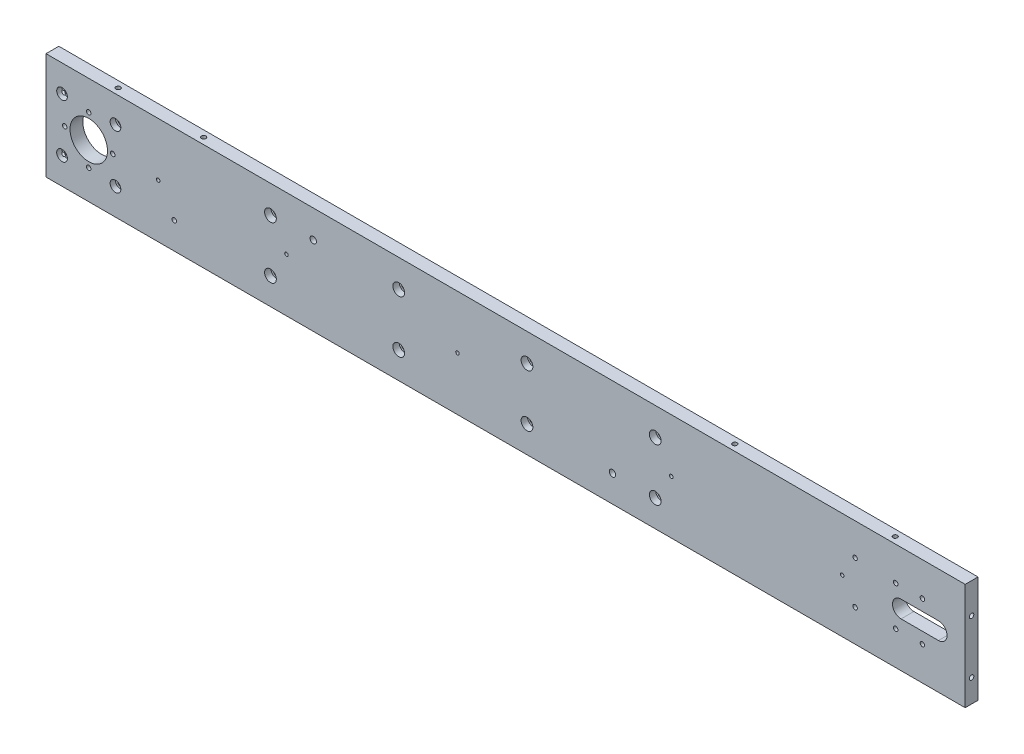
SolidWorks part; units mm, degrees
material "SKD11淬火HRC56-60"
ref_plane "前基準面" through (0, 0, 0) normal (0, 0, 1) x (1, 0, 0)
ref_plane "上基準面" through (0, 0, 0) normal (0, 1, 0) x (1, 0, 0)
ref_plane "右基準面" through (0, 0, 0) normal (1, 0, 0) x (0, 0, -1)
sketch "草图1" plane through (0, 0, 0) normal (0, 0, 1) x (1, 0, 0)
  line L1 (0, 0) -> (860, 0)
  line L2 (0, 0) -> (0, 100)
  line L3 (0, 100) -> (860, 100)
  line L4 (860, 0) -> (860, 100)
  dimension "D1" = 860
  dimension "D2" = 100
extrude "凸台-拉伸1" add sketch "草图1" along normal blind 12
sketch "草图2" plane through (0, 0, 12) normal (0, 0, 1) x (1, 0, 0)
  line L0 (0, 50) -> (860, 50) construction
  line L1 (0, 100) -> (0, 0) construction
  line L2 (430, 0) -> (430, 100) construction
  line L3 (0, 0) -> (860, 0) construction
  line L4 (860, 100) -> (0, 100) construction
  line L5 (860, 0) -> (860, 100) construction
  line L6 (800, 50) -> (835, 50) construction
  line L7 (800, 58) -> (835, 58)
  line L8 (800, 42) -> (835, 42)
  circle A0 centre (40, 50) radius 17.55
  arc A1 (800, 58) -> (800, 42) centre (800, 50) ccw
  arc A2 (835, 42) -> (835, 58) centre (835, 50) ccw
  point P14 (817.5, 50)
  dimension "D1" = 35.1
  dimension "D2" = 390
  dimension "D3" = 8
  dimension "D4" = 35
  dimension "D5" = 370
extrude "切除-拉伸1" cut sketch "草图2" against normal through all
hole_wizard "M5 螺纹孔1" positions "草图4" profile "草图3" tap size "M5" standard "ISO"
sketch "草图4" plane through (0, 100, 0) normal (0, 1, 0) x (-1, 0, 0)
  point P0 (-141.5, 6)
  point P5 (-61.5, 6)
  point P8 (-788.5, 6)
  point P11 (-638.5, 6)
sketch "草图3" plane through (141.5, 100, 6) normal (1, 0, 0) x (0, 0, 1)
  line L0 (0, 0) -> (0, 13.6618)
  line L1 (0, 13.6618) -> (2.1, 12.4)
  line L2 (2.1, 12.4) -> (2.1, 0)
  line L5 (2.1, 0) -> (0, 0)
  line L10 (0, 13.6618) -> (-2.1, 12.4) construction
  line L11 (0, -6.35) -> (0, 107.95) construction
  dimension "螺纹孔钻头直径" = 4.2
  dimension "螺纹孔钻头深度" = 12.4
  dimension "导头角度" = 118
cosmetic thread "孔螺蚊线1" parameters "D1"=10, "D2"=5
cosmetic thread "孔螺蚊线2" parameters "D1"=10, "D2"=5
cosmetic thread "孔螺蚊线3" parameters "D1"=10, "D2"=5
cosmetic thread "孔螺蚊线4" parameters "D1"=10, "D2"=5
hole_wizard "M5 螺纹孔2" positions "草图6" profile "草图5" tap size "M5" standard "ISO"
sketch "草图6" plane through (0, 0, 0) normal (-1, 0, 0) x (0, 0, 1)
  point P0 (6, 71.5)
  point P4 (6, 21.5)
sketch "草图5" plane through (0, 71.5, 6) normal (0, 1, 0) x (0, 0, 1)
  line L0 (0, 0) -> (0, 13.6618)
  line L1 (0, 13.6618) -> (2.1, 12.4)
  line L2 (2.1, 12.4) -> (2.1, 0)
  line L5 (2.1, 0) -> (0, 0)
  line L10 (0, 13.6618) -> (-2.1, 12.4) construction
  line L11 (0, -6.35) -> (0, 107.95) construction
  dimension "螺纹孔钻头直径" = 4.2
  dimension "螺纹孔钻头深度" = 12.4
  dimension "导头角度" = 118
cosmetic thread "孔螺蚊线5" parameters "D1"=10, "D2"=5
cosmetic thread "孔螺蚊线6" parameters "D1"=10, "D2"=5
hole_wizard "M5 螺纹孔3" positions "草图8" profile "草图7" tap size "M5" standard "ISO"
sketch "草图8" plane through (860, 0, 0) normal (1, 0, 0) x (0, 0, -1)
  point P0 (-6, 71.5)
  point P4 (-6, 21.5)
sketch "草图7" plane through (860, 71.5, 6) normal (0, 1, 0) x (0, 0, -1)
  line L0 (0, 0) -> (0, 13.6618)
  line L1 (0, 13.6618) -> (2.1, 12.4)
  line L2 (2.1, 12.4) -> (2.1, 0)
  line L5 (2.1, 0) -> (0, 0)
  line L10 (0, 13.6618) -> (-2.1, 12.4) construction
  line L11 (0, -6.35) -> (0, 107.95) construction
  dimension "螺纹孔钻头直径" = 4.2
  dimension "螺纹孔钻头深度" = 12.4
  dimension "导头角度" = 118
cosmetic thread "孔螺蚊线7" parameters "D1"=10, "D2"=5
cosmetic thread "孔螺蚊线8" parameters "D1"=10, "D2"=5
sketch "草图9" plane through (0, 0, 12) normal (0, 0, 1) x (1, 0, 0)
  line L0 (860, 100) -> (0, 100) construction
  line L1 (0, 100) -> (0, 0) construction
  circle A0 centre (250, 74) radius 3
  circle A1 centre (530, 25) radius 3
  dimension "D1" = 26
  dimension "D2" = 6
  dimension "D3" = 250
  dimension "D4" = 280
  dimension "D5" = 75
extrude "切除-拉伸2" cut sketch "草图9" against normal through all
hole_wizard "M6 六角凹头螺钉的柱形沉头孔1" positions "草图11" profile "草图10" counterbore size "M6" standard "ISO" end condition through all
sketch "草图11" plane through (0, 0, 12) normal (0, 0, 1) x (1, 0, 0)
  line L0 (860, 100) -> (0, 100) construction
  line L1 (0, 100) -> (0, 0) construction
  point P0 (210, 74)
  point P1 (330, 74)
  point P3 (450, 74)
  point P5 (570, 74)
  point P7 (570, 25)
  point P9 (450, 25)
  point P11 (330, 25)
  point P13 (210, 25)
  dimension "D1" = 26
  dimension "D2" = 75
  dimension "D3" = 210
  dimension "D4" = 120
  dimension "D5" = 120
  dimension "D6" = 120
sketch "草图10" plane through (210, 74, 12) normal (1, 0, 0) x (0, -1, 0)
  line L0 (0, 0) -> (0, 12)
  line L1 (0, 12) -> (3.5, 12)
  line L3 (3.5, 12) -> (3.5, 6)
  line L4 (3.5, 6) -> (5.5, 6)
  line L5 (5.5, 6) -> (5.5, 0)
  line L7 (5.5, 0) -> (0, 0)
  line L11 (0, -6.35) -> (0, 107.95) construction
  dimension "通孔孔直径" = 7
  dimension "通孔孔深度" = 12
  dimension "柱形沉头孔直径" = 11
  dimension "柱形沉头孔深度" = 6
hole_wizard "M4 螺纹孔1" positions "草图13" profile "草图12" tap size "M4" standard "ISO"
sketch "草图13" plane through (0, 0, 12) normal (0, 0, 1) x (1, 0, 0)
  point P5 (225, 50)
  point P8 (105, 50)
  point P11 (385, 50)
  point P14 (745, 50)
  point P17 (585, 50)
sketch "草图12" plane through (225, 50, 12) normal (1, 0, 0) x (0, -1, 0)
  line L0 (0, 0) -> (0, 11.0914)
  line L1 (0, 11.0914) -> (1.65, 10.1)
  line L2 (1.65, 10.1) -> (1.65, 0)
  line L5 (1.65, 0) -> (0, 0)
  line L10 (0, 11.0914) -> (-1.65, 10.1) construction
  line L11 (0, -6.35) -> (0, 107.95) construction
  dimension "螺纹孔钻头直径" = 3.3
  dimension "螺纹孔钻头深度" = 10.1
  dimension "导头角度" = 118
cosmetic thread "孔螺蚊线9" parameters "D1"=8, "D2"=4
cosmetic thread "孔螺蚊线10" parameters "D1"=8, "D2"=4
cosmetic thread "孔螺蚊线11" parameters "D1"=8, "D2"=4
cosmetic thread "孔螺蚊线12" parameters "D1"=8, "D2"=4
cosmetic thread "孔螺蚊线13" parameters "D1"=8, "D2"=4
hole_wizard "M5 螺纹孔4" positions "草图15" profile "草图14" tap size "M5" standard "ISO"
sketch "草图15" plane through (0, 0, 0) normal (0, 0, -1) x (-1, 0, 0)
  point P0 (-757, 70)
  point P1 (-757, 30)
sketch "草图14" plane through (757, 70, 0) normal (1, 0, 0) x (0, 1, 0)
  line L0 (0, 0) -> (0, 13.6618)
  line L1 (0, 13.6618) -> (2.1, 12.4)
  line L2 (2.1, 12.4) -> (2.1, 0)
  line L5 (2.1, 0) -> (0, 0)
  line L10 (0, 13.6618) -> (-2.1, 12.4) construction
  line L11 (0, -6.35) -> (0, 107.95) construction
  dimension "螺纹孔钻头直径" = 4.2
  dimension "螺纹孔钻头深度" = 12.4
  dimension "导头角度" = 118
cosmetic thread "孔螺蚊线14" parameters "D1"=10, "D2"=5
cosmetic thread "孔螺蚊线15" parameters "D1"=10, "D2"=5
hole_wizard "M5 螺纹孔5" positions "草图17" profile "草图16" tap size "M5" standard "ISO"
sketch "草图17" plane through (0, 0, 0) normal (0, 0, -1) x (-1, 0, 0)
  line L0 (-860, 0) -> (-860, 100) construction
  line L1 (-860, 100) -> (0, 100) construction
  point P0 (-795, 68.5)
  point P1 (-820, 68.5)
  point P3 (-795, 31.5)
  point P5 (-820, 31.5)
  dimension "D1" = 40
  dimension "D2" = 25
  dimension "D3" = 37
  dimension "D4" = 31.5
sketch "草图16" plane through (795, 68.5, 0) normal (1, 0, 0) x (0, 1, 0)
  line L0 (0, 0) -> (0, 13.6618)
  line L1 (0, 13.6618) -> (2.1, 12.4)
  line L2 (2.1, 12.4) -> (2.1, 0)
  line L5 (2.1, 0) -> (0, 0)
  line L10 (0, 13.6618) -> (-2.1, 12.4) construction
  line L11 (0, -6.35) -> (0, 107.95) construction
  dimension "螺纹孔钻头直径" = 4.2
  dimension "螺纹孔钻头深度" = 12.4
  dimension "导头角度" = 118
cosmetic thread "孔螺蚊线16" parameters "D1"=10, "D2"=5
cosmetic thread "孔螺蚊线17" parameters "D1"=10, "D2"=5
cosmetic thread "孔螺蚊线18" parameters "D1"=10, "D2"=5
cosmetic thread "孔螺蚊线19" parameters "D1"=10, "D2"=5
hole_wizard "M5 六角凹头螺钉的柱形沉头孔1" positions "草图19" profile "草图18" counterbore size "M5" standard "ISO" end condition through all
sketch "草图19" plane through (0, 0, 12) normal (0, 0, 1) x (1, 0, 0)
  point P4 (15, 25)
  point P7 (15, 75)
  point P11 (65, 75)
  point P14 (65, 25)
sketch "草图18" plane through (15, 25, 12) normal (1, 0, 0) x (0, -1, 0)
  line L0 (0, 0) -> (0, 12)
  line L1 (0, 12) -> (2.9, 12)
  line L3 (2.9, 12) -> (2.9, 5)
  line L4 (2.9, 5) -> (5, 5)
  line L5 (5, 5) -> (5, 0)
  line L7 (5, 0) -> (0, 0)
  line L11 (0, -6.35) -> (0, 107.95) construction
  dimension "通孔孔直径" = 5.8
  dimension "通孔孔深度" = 12
  dimension "柱形沉头孔直径" = 10
  dimension "柱形沉头孔深度" = 5
hole_wizard "M5 螺纹孔6" positions "草图21" profile "草图20" tap size "M5" standard "ISO"
sketch "草图21" plane through (0, 0, 0) normal (0, 0, -1) x (-1, 0, 0)
  point P0 (-17.5, 50)
  point P1 (-40, 27.5)
  point P4 (-40, 72.5)
  point P7 (-62.5, 50)
sketch "草图20" plane through (17.5, 50, 0) normal (1, 0, 0) x (0, 1, 0)
  line L0 (0, 0) -> (0, 13.6618)
  line L1 (0, 13.6618) -> (2.1, 12.4)
  line L2 (2.1, 12.4) -> (2.1, 0)
  line L5 (2.1, 0) -> (0, 0)
  line L10 (0, 13.6618) -> (-2.1, 12.4) construction
  line L11 (0, -6.35) -> (0, 107.95) construction
  dimension "螺纹孔钻头直径" = 4.2
  dimension "螺纹孔钻头深度" = 12.4
  dimension "导头角度" = 118
cosmetic thread "孔螺蚊线20" parameters "D1"=10, "D2"=5
cosmetic thread "孔螺蚊线21" parameters "D1"=10, "D2"=5
cosmetic thread "孔螺蚊线22" parameters "D1"=10, "D2"=5
cosmetic thread "孔螺蚊线23" parameters "D1"=10, "D2"=5
hole_wizard "M5 螺纹孔7" positions "草图23" profile "草图22" tap size "M5" standard "ISO"
sketch "草图23" plane through (0, 0, 0) normal (0, 0, -1) x (-1, 0, 0)
  line L0 (0, 0) -> (-860, 0) construction
  line L1 (0, 100) -> (0, 0) construction
  point P0 (-120, 25)
  dimension "D1" = 25
  dimension "D2" = 120
sketch "草图22" plane through (120, 25, 0) normal (1, 0, 0) x (0, 1, 0)
  line L0 (0, 0) -> (0, 13.6618)
  line L1 (0, 13.6618) -> (2.1, 12.4)
  line L2 (2.1, 12.4) -> (2.1, 0)
  line L5 (2.1, 0) -> (0, 0)
  line L10 (0, 13.6618) -> (-2.1, 12.4) construction
  line L11 (0, -6.35) -> (0, 107.95) construction
  dimension "螺纹孔钻头直径" = 4.2
  dimension "螺纹孔钻头深度" = 12.4
  dimension "导头角度" = 118
cosmetic thread "孔螺蚊线24" parameters "D1"=10, "D2"=5
hole_wizard "M3 螺纹孔1" positions "草图25" profile "草图24" tap size "M3" standard "ISO"
sketch "草图25" plane through (0, 0, 0) normal (0, -1, 0) x (1, 0, 0)
  line L0 (0, 6) -> (159.297, 6) construction
  line L1 (0, 12) -> (0, 0) construction
  point P0 (120, 6)
  point P1 (140, 6)
  point P3 (160, 6)
  point P5 (680, 6)
  point P7 (700, 6)
  point P9 (720, 6)
  point P11 (90, 6)
  point P13 (70, 6)
  dimension "D1" = 720
  dimension "D2" = 700
  dimension "D3" = 680
  dimension "D4" = 160
  dimension "D5" = 140
  dimension "D6" = 120
  dimension "D7" = 90
  dimension "D8" = 70
sketch "草图24" plane through (120, 0, 6) normal (1, 0, 0) x (0, 0, -1)
  line L0 (0, 0) -> (0, 8.2511)
  line L1 (0, 8.2511) -> (1.25, 7.5)
  line L2 (1.25, 7.5) -> (1.25, 0)
  line L5 (1.25, 0) -> (0, 0)
  line L10 (0, 8.2511) -> (-1.25, 7.5) construction
  line L11 (0, -6.35) -> (0, 107.95) construction
  dimension "螺纹孔钻头直径" = 2.5
  dimension "螺纹孔钻头深度" = 7.5
  dimension "导头角度" = 118
cosmetic thread "孔螺蚊线25" parameters "D1"=6, "D2"=3
cosmetic thread "孔螺蚊线26" parameters "D1"=6, "D2"=3
cosmetic thread "孔螺蚊线27" parameters "D1"=6, "D2"=3
cosmetic thread "孔螺蚊线28" parameters "D1"=6, "D2"=3
cosmetic thread "孔螺蚊线29" parameters "D1"=6, "D2"=3
cosmetic thread "孔螺蚊线30" parameters "D1"=6, "D2"=3
cosmetic thread "孔螺蚊线31" parameters "D1"=6, "D2"=3
cosmetic thread "孔螺蚊线32" parameters "D1"=6, "D2"=3
